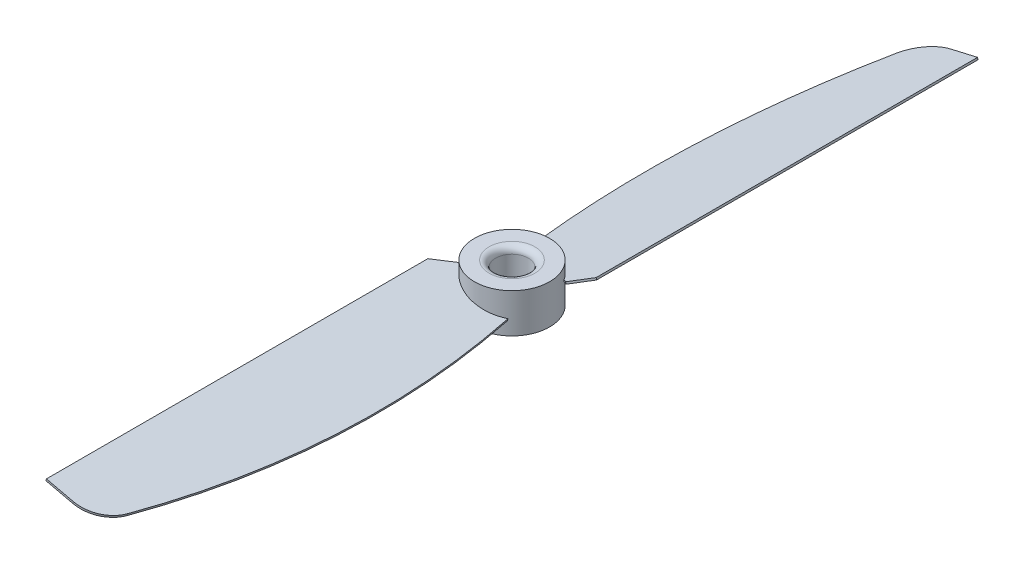
SolidWorks part; units mm, degrees
ref_plane "Front Plane" through (0, 0, 0) normal (0, 0, 1) x (1, 0, 0)
ref_plane "Top Plane" through (0, 0, 0) normal (0, 1, 0) x (1, 0, 0)
ref_plane "Right Plane" through (0, 0, 0) normal (1, 0, 0) x (0, 0, -1)
sketch "Sketch1" plane through (0, 0, 0) normal (0, 1, 0) x (1, 0, 0)
  circle A0 centre (0, 0) radius 5.75
  dimension "D1" = 11.5
extrude "Boss-Extrude2" add sketch "Sketch1" along normal mid plane 6
sketch "Sketch4" plane through (0, 0, 0) normal (0, 0, 1) x (1, 0, 0)
  line L0 (-7.8224, 1.8059) -> (7.8224, -1.8059) construction
  line L1 (-5.75, -3) -> (5.75, -3) construction
  dimension "D1" = 13
ref_plane "Plane2" through (0, 0, 0) normal (-0.225, -0.9744, 0) x (0.9744, -0.225, 0)
sketch "Sketch6" plane through (0, 0, 0) normal (-0.225, -0.9744, 0) x (0.9744, -0.225, 0)
  line L0 (-5.5574, 2.82) -> (-7.9209, 5.18)
  line L1 (-7.9209, 5.18) -> (-7.9209, 63.5)
  line L2 (-7.9209, 63.5) -> (-3.7109, 63.5)
  arc A0 (-3.7109, 63.5) -> (1.1001, 59.8617) centre (-3.7109, 58.5) cw
  arc A1 (1.1001, 59.8617) -> (2.4708, -2.12) centre (-117.7318, 26.2278) cw
  arc A2 (-5.5574, 2.82) -> (2.4708, -2.12) centre (-2.87, -1.806) cw
  ellipse E0 centre (-0.6749, 0) end of major axis (-0.6749, 5.75) minor radius 5.6026 construction
  point P16 (-1.0999, 150.1399)
  point P17 (4.1901, 150.5414)
  dimension "D5" = 5.35
  dimension "D6" = 123.5
  dimension "D7" = 5
  dimension "D1" = 2.82
  dimension "D2" = 5.18
  dimension "D3" = 3.34
  dimension "D4" = 2.87
  dimension "D8" = 63.5
  dimension "D9" = 65.62
  dimension "D10" = 4.21
extrude "Boss-Extrude3" add sketch "Sketch6" along normal mid plane 0.3
pattern_circular "CirPattern1" count 2 every 180 about axis through (0, 0, 0) along (0, 1, 0) of "Boss-Extrude3"
sketch "Sketch7" plane through (0, 3, 0) normal (0, 1, 0) x (1, 0, 0)
  circle A0 centre (0, 0) radius 2.5
  dimension "D1" = 5
extrude "Cut-Extrude1" cut sketch "Sketch7" against normal through all
fillet "Fillet1" radius 1 2 edges at (0, -3, 2.5) (0, 3, 2.5)
